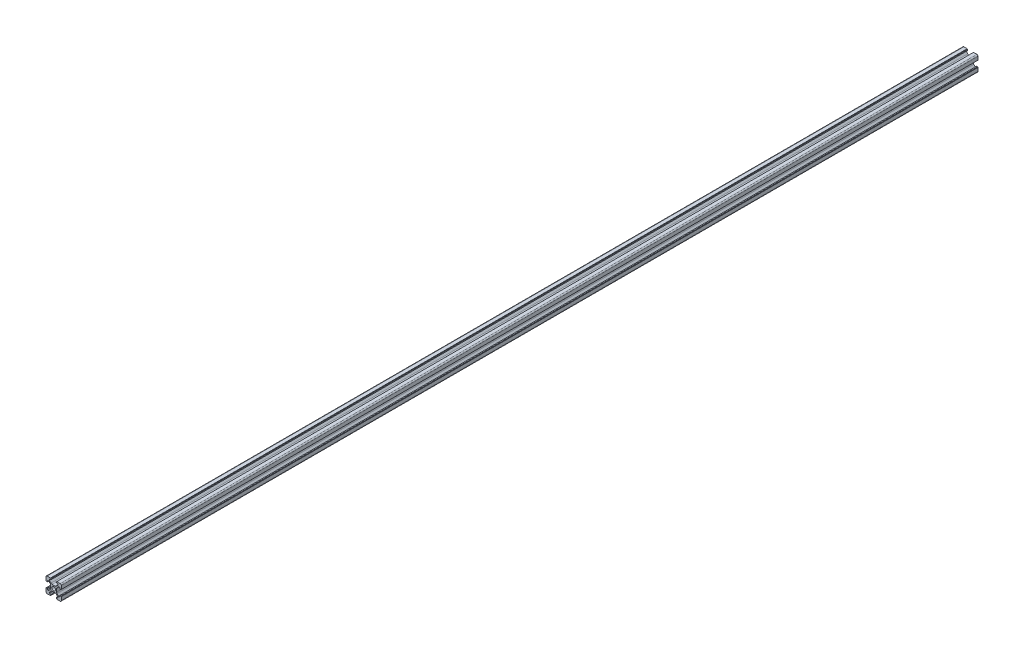
SolidWorks part; units mm, degrees
material "6063-O"
ref_plane "Front Plane" through (0, 0, 0) normal (0, 0, 1) x (1, 0, 0)
ref_plane "Top Plane" through (0, 0, 0) normal (0, 1, 0) x (1, 0, 0)
ref_plane "Right Plane" through (0, 0, 0) normal (1, 0, 0) x (0, 0, -1)
sketch "Sketch1" plane through (0, 0, 0) normal (0, 0, 1) x (1, 0, 0)
  line L0 (10, -4.1) -> (10, -8.5)
  line L1 (4.1, 10) -> (8.5, 10)
  line L2 (8.5, -10) -> (4.1, -10)
  line L3 (-8.5, -10) -> (-4.1, -10)
  line L4 (10, 8.5) -> (10, 4.1)
  line L7 (8.5, 10) -> (4.1, 10)
  line L8 (5.5, 6.5607) -> (3.4251, 4.4858)
  line L9 (8.5, 10) -> (4.1, 10)
  line L10 (3.9, 2.0109) -> (3.9, -2.0109)
  line L11 (2.0109, -3.9) -> (-2.0109, -3.9)
  line L12 (-3.9, -2.0109) -> (-3.9, 2.0109)
  line L13 (-2.0109, 3.9) -> (2.8393, 3.9)
  line L14 (2.5, 0) -> (22.2403, 0) construction
  line L15 (3.6, 9.5) -> (3.6, 8.2)
  line L16 (9.5, 3.6) -> (8.2, 3.6)
  line L17 (8.2, 3.6) -> (8.2, 5.5)
  line L18 (8.2, 5.5) -> (6.5607, 5.5)
  line L19 (10, -4.1) -> (10, -8.5)
  line L20 (4.1, 9.5) -> (3.6, 9.5)
  line L21 (4.1, 10) -> (4.1, 9.5)
  line L22 (8.5, 10) -> (4.1, 10)
  line L23 (10, 4.1) -> (9.5, 4.1)
  line L24 (9.5, 4.1) -> (9.5, 3.6)
  line L25 (5.5, 8.2) -> (5.5, 6.5607)
  line L26 (3.6, 8.2) -> (5.5, 8.2)
  line L27 (4.4858, 3.4251) -> (6.5607, 5.5)
  line L28 (10, -8.5) -> (10, -4.1)
  line L29 (6.5607, -5.5) -> (4.4858, -3.4251)
  line L30 (10, -8.5) -> (10, -4.1)
  line L31 (2.0109, -3.9) -> (-2.0109, -3.9)
  line L32 (3.9, 2.8393) -> (3.9, -2.0109)
  line L33 (9.5, -3.6) -> (8.2, -3.6)
  line L34 (3.6, -9.5) -> (3.6, -8.2)
  line L35 (3.6, -8.2) -> (5.5, -8.2)
  line L36 (5.5, -8.2) -> (5.5, -6.5607)
  line L37 (9.5, -4.1) -> (9.5, -3.6)
  line L38 (10, -4.1) -> (9.5, -4.1)
  line L39 (10, -8.5) -> (10, -4.1)
  line L40 (4.1, -10) -> (4.1, -9.5)
  line L41 (4.1, -9.5) -> (3.6, -9.5)
  line L42 (8.2, -5.5) -> (6.5607, -5.5)
  line L43 (8.2, -3.6) -> (8.2, -5.5)
  line L44 (3.4251, -4.4858) -> (5.5, -6.5607)
  line L45 (-4.1, -10) -> (-8.5, -10)
  line L46 (-10, -8.5) -> (-10, -4.1)
  line L47 (-8.5, -10) -> (-4.1, -10)
  line L48 (-5.5, -6.5607) -> (-3.4251, -4.4858)
  line L49 (-8.5, -10) -> (-4.1, -10)
  line L50 (-3.9, -2.0109) -> (-3.9, 2.0109)
  line L51 (2.0109, -3.9) -> (-2.0109, -3.9)
  line L52 (-3.6, -9.5) -> (-3.6, -8.2)
  line L53 (-9.5, -3.6) -> (-8.2, -3.6)
  line L54 (-8.2, -3.6) -> (-8.2, -5.5)
  line L55 (-8.2, -5.5) -> (-6.5607, -5.5)
  line L56 (-4.1, -9.5) -> (-3.6, -9.5)
  line L57 (-4.1, -10) -> (-4.1, -9.5)
  line L58 (-8.5, -10) -> (-4.1, -10)
  line L59 (-10, -4.1) -> (-9.5, -4.1)
  line L60 (-9.5, -4.1) -> (-9.5, -3.6)
  line L61 (-5.5, -8.2) -> (-5.5, -6.5607)
  line L62 (-3.6, -8.2) -> (-5.5, -8.2)
  line L63 (-4.4858, -3.4251) -> (-6.5607, -5.5)
  line L64 (-10, 4.1) -> (-10, 8.5)
  line L65 (-8.5, 10) -> (-4.1, 10)
  line L66 (-10, 8.5) -> (-10, 4.1)
  line L67 (-6.5607, 5.5) -> (-4.4858, 3.4251)
  line L68 (-10, 8.5) -> (-10, 4.1)
  line L69 (-2.0109, 3.9) -> (2.0109, 3.9)
  line L70 (-3.9, -2.0109) -> (-3.9, 2.0109)
  line L71 (-9.5, 3.6) -> (-8.2, 3.6)
  line L72 (-3.6, 9.5) -> (-3.6, 8.2)
  line L73 (-3.6, 8.2) -> (-5.5, 8.2)
  line L74 (-5.5, 8.2) -> (-5.5, 6.5607)
  line L75 (-9.5, 4.1) -> (-9.5, 3.6)
  line L76 (-10, 4.1) -> (-9.5, 4.1)
  line L77 (-10, 8.5) -> (-10, 4.1)
  line L78 (-4.1, 10) -> (-4.1, 9.5)
  line L79 (-4.1, 9.5) -> (-3.6, 9.5)
  line L80 (-8.2, 5.5) -> (-6.5607, 5.5)
  line L81 (-8.2, 3.6) -> (-8.2, 5.5)
  line L82 (-3.4251, 4.4858) -> (-5.5, 6.5607)
  line L83 (4.1, -10) -> (8.5, -10)
  arc A0 (2.0109, -3.9) -> (3.4251, -4.4858) centre (2.0109, -5.9) cw
  arc A1 (4.4858, -3.4251) -> (3.9, -2.0109) centre (5.9, -2.0109) cw
  arc A2 (3.9, 2.0109) -> (4.4858, 3.4251) centre (5.9, 2.0109) cw
  arc A3 (2.0109, 3.9) -> (3.4251, 4.4858) centre (2.0109, 5.9) ccw
  arc A4 (-2.0109, 3.9) -> (-3.4251, 4.4858) centre (-2.0109, 5.9) cw
  arc A5 (-4.4858, 3.4251) -> (-3.9, 2.0109) centre (-5.9, 2.0109) cw
  arc A6 (-3.4251, -4.4858) -> (-2.0109, -3.9) centre (-2.0109, -5.9) cw
  arc A7 (-3.9, -2.0109) -> (-4.4858, -3.4251) centre (-5.9, -2.0109) cw
  circle A8 centre (0, 0) radius 2.5
  arc A9 (-8.5, -10) -> (-10, -8.5) centre (-8.5, -8.5) cw
  arc A10 (-10, 8.5) -> (-8.5, 10) centre (-8.5, 8.5) cw
  arc A11 (8.5, 10) -> (10, 8.5) centre (8.5, 8.5) cw
  arc A12 (8.5, -10) -> (10, -8.5) centre (8.5, -8.5) ccw
  point P0 (0, 0)
  point P86 (0, 0)
  point P107 (10, -10)
  dimension "D3" = 2
  dimension "D5" = 5
  dimension "D2" = 1.5
  dimension "D8" = 1.5
  dimension "D6" = 4
  dimension "D7" = 6.1
  dimension "D11" = 0.5
  dimension "D12" = 0.5
extrude "Boss-Extrude2" add sketch "Sketch1" along normal blind 1200
